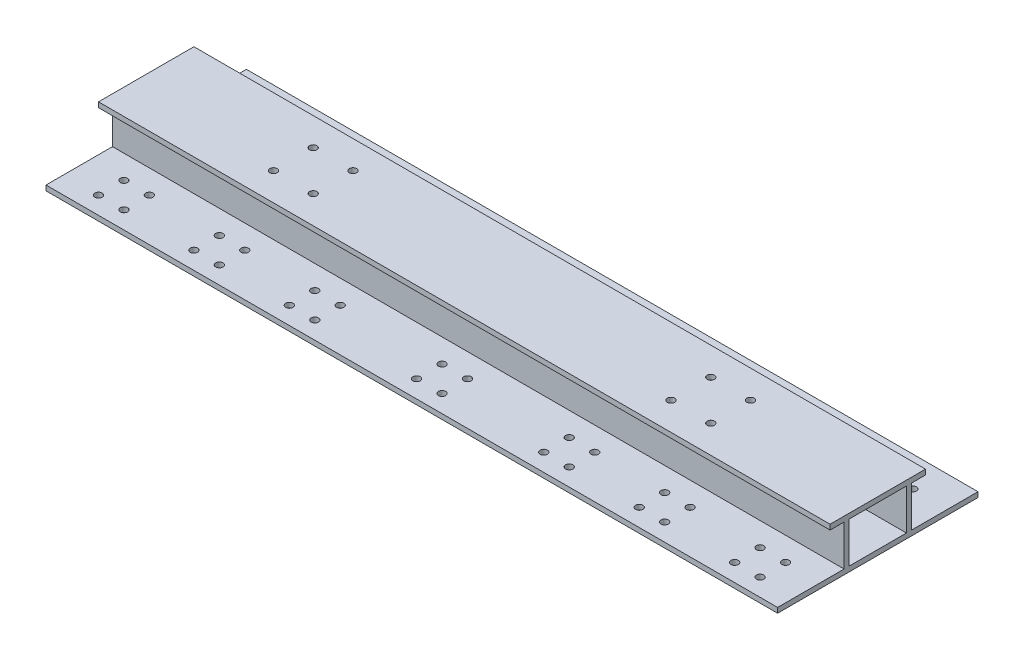
SolidWorks part; units mm, degrees
ref_plane "前视基准面" through (0, 0, 0) normal (0, 0, 1) x (1, 0, 0)
ref_plane "上视基准面" through (0, 0, 0) normal (0, 1, 0) x (1, 0, 0)
ref_plane "右视基准面" through (0, 0, 0) normal (1, 0, 0) x (0, 0, -1)
sketch "草图7" plane through (0, 0, 0) normal (1, 0, 0) x (0, 0, -1)
  line L0 (0, -1000) -> (0, 49000) construction
  line L1 (-1000, 0) -> (49000, 0) construction
  line L2 (-315, 16) -> (-315, 0)
  line L3 (-315, 0) -> (315, 0)
  line L4 (315, 0) -> (315, 16)
  line L5 (315, 16) -> (106, 16)
  line L6 (-106, 144) -> (-106, 16)
  line L7 (106, 144) -> (150, 144)
  line L8 (150, 144) -> (150, 160)
  line L9 (150, 160) -> (-150, 160)
  line L10 (-150, 160) -> (-150, 144)
  line L11 (-150, 144) -> (-106, 144)
  line L12 (106, 144) -> (106, 16)
  line L13 (-106, 16) -> (-315, 16)
  line L14 (-90, 144) -> (-90, 16)
  line L15 (-90, 16) -> (90, 16)
  line L16 (90, 16) -> (90, 144)
  line L17 (90, 144) -> (-90, 144)
  dimension "D1" = 630
  dimension "D2" = 16
  dimension "D3" = 16
  dimension "D4" = 16
  dimension "D5" = 16
  dimension "D6" = 160
  dimension "D7" = 300
  dimension "D8" = 180
extrude "凸台-拉伸1" add sketch "草图7" along normal blind 2300
sketch "草图8" plane through (0, 160, 0) normal (0, 1, 0) x (1, 0, 0)
  line L0 (1300, 0) -> (51300, 0) construction
  line L1 (2300, 150) -> (2300, -150) construction
  line L3 (1150, -850) -> (1150, 49150) construction
  line L4 (2300, 150) -> (0, 150) construction
  circle A0 centre (462.5, 62.5) radius 11.5
  circle A1 centre (587.5, 62.5) radius 11.5
  circle A2 centre (462.5, -62.5) radius 11.5
  circle A3 centre (587.5, -62.5) radius 11.5
  circle A4 centre (1712.5, 62.5) radius 11.5
  circle A5 centre (1837.5, 62.5) radius 11.5
  circle A6 centre (1712.5, -62.5) radius 11.5
  circle A7 centre (1837.5, -62.5) radius 11.5
  point P6 (2300, 0)
  point P12 (1150, 150)
  dimension "D1" = 23
  dimension "D2" = 125
  dimension "D3" = 125
  dimension "D4" = 1125
extrude "切除-拉伸1" cut sketch "草图8" against normal blind 16
sketch "草图9" plane through (0, 0, 0) normal (0, -1, 0) x (1, 0, 0)
  line L0 (1300, 0) -> (51300, 0) construction
  line L1 (2300, 315) -> (2300, -315) construction
  line L2 (1233.4867, 180) -> (51233.4867, 180) construction
  line L3 (1282.0714, -140) -> (51282.0714, -140) construction
  line L4 (-935.8177, 260) -> (49064.1823, 260) construction
  line L5 (-879.9453, -220) -> (49120.0547, -220) construction
  line L7 (2190, -911.5364) -> (2190, 49088.4636) construction
  line L8 (2110, -921.8638) -> (2110, 49078.1362) construction
  line L9 (1890, -921.8638) -> (1890, 49078.1362) construction
  line L10 (1810, -925.3063) -> (1810, 49074.6937) construction
  line L11 (1590, -932.1912) -> (1590, 49067.8088) construction
  line L12 (1510, -942.5186) -> (1510, 49057.4814) construction
  line L13 (1190, -942.5186) -> (1190, 49057.4814) construction
  line L14 (1110, -942.5186) -> (1110, 49057.4814) construction
  line L15 (790, -935.6336) -> (790, 49064.3664) construction
  line L16 (710, -921.8638) -> (710, 49078.1362) construction
  line L17 (490, -921.8638) -> (490, 49078.1362) construction
  line L18 (410, -925.3063) -> (410, 49074.6937) construction
  line L19 (190, -928.7487) -> (190, 49071.2513) construction
  line L20 (110, -939.0761) -> (110, 49060.9239) construction
  line L21 (0, 315) -> (0, -315) construction
  circle A0 centre (110, 260) radius 11.5
  circle A1 centre (190, 260) radius 11.5
  circle A2 centre (410, 260) radius 11.5
  circle A3 centre (490, 260) radius 11.5
  circle A4 centre (710, 260) radius 11.5
  circle A5 centre (790, 260) radius 11.5
  circle A6 centre (1110, 260) radius 11.5
  circle A7 centre (1190, 260) radius 11.5
  circle A8 centre (1510, 260) radius 11.5
  circle A9 centre (1590, 260) radius 11.5
  circle A10 centre (1810, 260) radius 11.5
  circle A11 centre (1890, 260) radius 11.5
  circle A12 centre (110, 180) radius 11.5
  circle A13 centre (190, 180) radius 11.5
  circle A14 centre (410, 180) radius 11.5
  circle A15 centre (490, 180) radius 11.5
  circle A16 centre (710, 180) radius 11.5
  circle A17 centre (790, 180) radius 11.5
  circle A18 centre (1110, 180) radius 11.5
  circle A19 centre (1190, 180) radius 11.5
  circle A20 centre (1510, 180) radius 11.5
  circle A21 centre (1590, 180) radius 11.5
  circle A22 centre (1810, 180) radius 11.5
  circle A23 centre (1890, 180) radius 11.5
  circle A24 centre (110, -140) radius 11.5
  circle A25 centre (190, -140) radius 11.5
  circle A26 centre (410, -140) radius 11.5
  circle A27 centre (490, -140) radius 11.5
  circle A28 centre (710, -140) radius 11.5
  circle A29 centre (790, -140) radius 11.5
  circle A30 centre (1110, -140) radius 11.5
  circle A31 centre (1190, -140) radius 11.5
  circle A32 centre (1510, -140) radius 11.5
  circle A33 centre (1590, -140) radius 11.5
  circle A34 centre (1810, -140) radius 11.5
  circle A35 centre (1890, -140) radius 11.5
  circle A36 centre (110, -220) radius 11.5
  circle A37 centre (190, -220) radius 11.5
  circle A38 centre (410, -220) radius 11.5
  circle A39 centre (490, -220) radius 11.5
  circle A40 centre (710, -220) radius 11.5
  circle A41 centre (790, -220) radius 11.5
  circle A42 centre (1110, -220) radius 11.5
  circle A43 centre (1190, -220) radius 11.5
  circle A44 centre (1510, -220) radius 11.5
  circle A45 centre (1590, -220) radius 11.5
  circle A46 centre (1810, -220) radius 11.5
  circle A47 centre (1890, -220) radius 11.5
  circle A48 centre (2110, 260) radius 11.5
  circle A49 centre (2190, 260) radius 11.5
  circle A50 centre (2110, 180) radius 11.5
  circle A51 centre (2190, 180) radius 11.5
  circle A52 centre (2110, -140) radius 11.5
  circle A53 centre (2190, -140) radius 11.5
  circle A54 centre (2110, -220) radius 11.5
  circle A55 centre (2190, -220) radius 11.5
  point P5 (2300, 0)
  dimension "D19" = 23
  dimension "D1" = 180
  dimension "D2" = 140
  dimension "D3" = 80
  dimension "D4" = 80
  dimension "D5" = 110
  dimension "D6" = 80
  dimension "D7" = 220
  dimension "D8" = 80
  dimension "D9" = 220
  dimension "D10" = 80
  dimension "D11" = 320
  dimension "D12" = 80
  dimension "D13" = 320
  dimension "D14" = 80
  dimension "D15" = 220
  dimension "D16" = 80
  dimension "D17" = 220
  dimension "D18" = 80
extrude "切除-拉伸2" cut sketch "草图9" against normal blind 16
